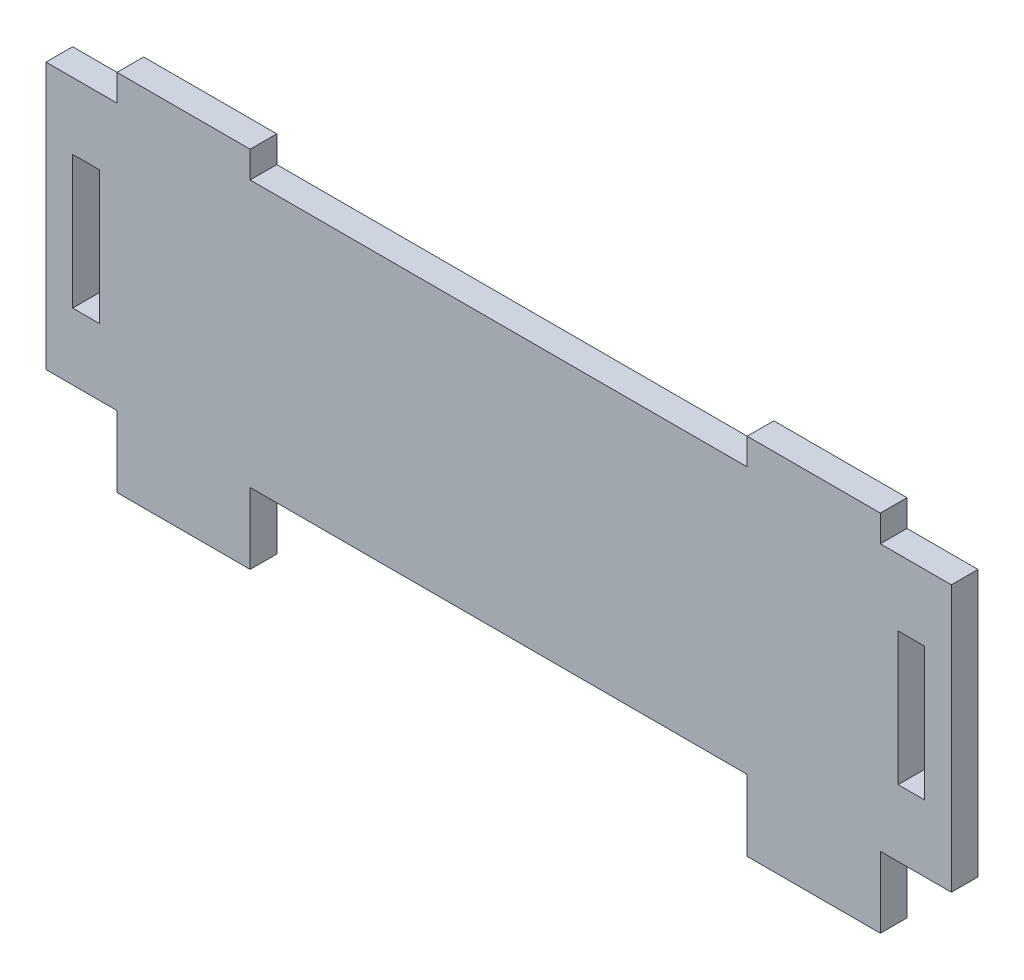
SolidWorks part; units mm, degrees
ref_plane "Front Plane" through (0, 0, 0) normal (0, 0, 1) x (1, 0, 0)
ref_plane "Top Plane" through (0, 0, 0) normal (0, 1, 0) x (1, 0, 0)
ref_plane "Right Plane" through (0, 0, 0) normal (1, 0, 0) x (0, 0, -1)
sketch "Sketch1" plane through (0, 0, 0) normal (0, 0, 1) x (1, 0, 0)
  line L0 (-51, 15) -> (-43, 15)
  line L6 (51, -15) -> (51, 15)
  line L8 (-51, -15) -> (-51, 15)
  line L9 (-43, 15) -> (-43, 18)
  line L10 (-43, 18) -> (-28, 18)
  line L15 (-28, 18) -> (-28, 15)
  line L16 (-28, 15) -> (28, 15)
  line L19 (28, 18) -> (43, 18)
  line L21 (28, 15) -> (28, 18)
  line L22 (43, 18) -> (43, 15)
  line L23 (-43, -23) -> (-28, -23)
  line L27 (43, 15) -> (51, 15)
  line L28 (51, -15) -> (43, -15)
  line L29 (43, -23) -> (28, -23)
  line L30 (43, -15) -> (43, -23)
  line L32 (28, -23) -> (28, -15)
  line L33 (28, -15) -> (-28, -15)
  line L34 (-28, -15) -> (-28, -23)
  line L35 (-43, -23) -> (-43, -15)
  line L36 (-43, -15) -> (-51, -15)
  line L38 (-48, 7.5) -> (-45, 7.5)
  line L39 (-48, 7.5) -> (-48, -7.5)
  line L40 (-48, -7.5) -> (-45, -7.5)
  line L41 (-45, 7.5) -> (-45, -7.5)
  line L44 (45, 7.5) -> (48, 7.5)
  line L45 (45, 7.5) -> (45, -7.5)
  line L46 (45, -7.5) -> (48, -7.5)
  line L47 (48, 7.5) -> (48, -7.5)
  point P0 (0, 0)
  point P2 (-28, 15)
  point P13 (-43, 15)
  point P14 (-43, -15)
  point P15 (-51, 15)
  point P16 (-51, -15)
  point P17 (-28, -15)
  point P24 (0, 0)
  point P28 (-43, -23)
  point P29 (-28, 18)
  point P30 (-43, 18)
  point P31 (-28, -23)
  point P32 (28, -15)
  point P33 (43, -15)
  point P34 (28, -23)
  point P35 (43, -23)
  point P36 (43, 15)
  point P37 (51, -15)
  point P38 (51, 15)
  point P39 (28, 15)
  point P40 (43, 18)
  point P41 (28, 18)
  point P47 (0, 0)
  point P52 (0, 0)
  point P53 (0, 0)
  point P54 (0, 0)
  point P55 (0, 0)
  point P56 (0, 0)
  point P57 (0, 0)
  point P58 (0, 0)
  point P59 (0, 0)
  point P60 (0, 0)
  point P61 (0, 0)
  point P62 (0, 0)
  point P63 (0, 0)
  point P64 (0, 0)
  point P65 (0, 0)
  point P66 (0, 0)
  point P67 (0, 0)
  point P68 (0, 0)
  point P69 (0, 0)
  point P70 (0, 0)
  point P71 (0, 0)
  point P72 (0, 0)
  point P73 (0, 0)
  point P74 (0, 0)
  point P75 (0, 0)
  point P76 (0, 0)
  point P77 (0, 0)
  point P78 (0, 0)
  point P79 (0, 0)
  point P80 (0, 0)
  point P81 (0, 0)
extrude "Boss-Extrude1" add sketch "Sketch1" along normal blind 3 contours L8 L0 L9 L10 L15 L16 L21 L19 L22 L27 L6 L28 L30 L29 L32 L33 L34 L23 L35 L36 | L41 L40 L39 L38 | L47 L46 L45 L44
